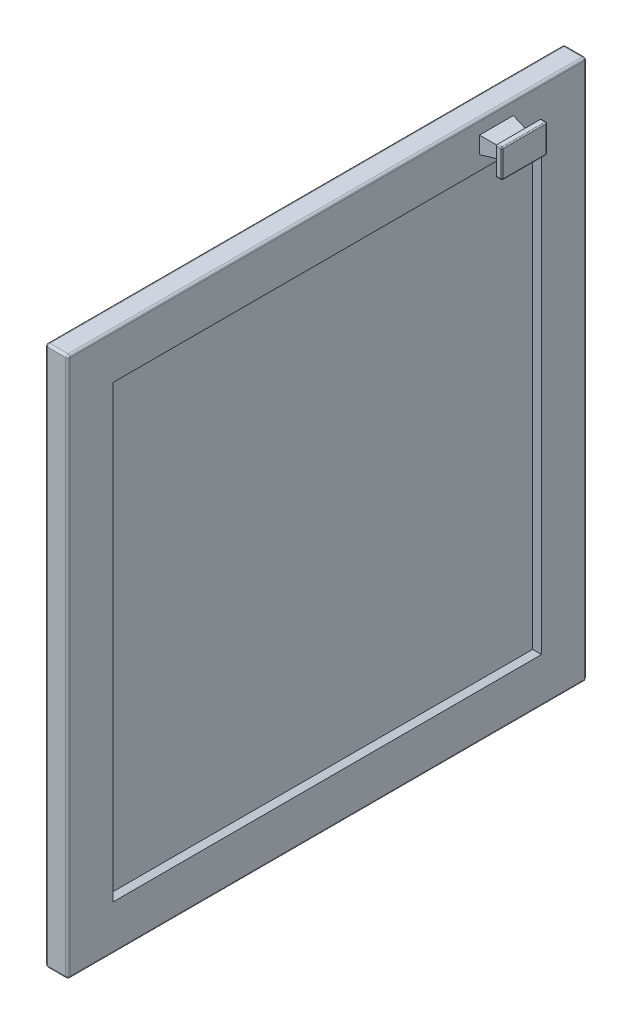
SolidWorks part; units mm, degrees
ref_plane "Front Plane" through (0, 0, 0) normal (1, 0, 0) x (0, 1, 0)
ref_plane "Top Plane" through (0, 0, 0) normal (0, 0, 1) x (0, 1, 0)
ref_plane "Right Plane" through (0, 0, 0) normal (0, 1, 0) x (-1, 0, 0)
sketch "Sketch1" plane through (0, 0, 0) normal (1, 0, 0) x (0, 1, 0)
  line L1 (0, 0) -> (479, 0)
  line L2 (0, 0) -> (0, 460)
  line L3 (0, 460) -> (479, 460)
  line L4 (479, 0) -> (479, 460)
  dimension "D1" = 460
  dimension "D2" = 479
extrude "Boss-Extrude1" add sketch "Sketch1" along normal mid plane 20
sketch "Sketch2" plane through (10, 0, 0) normal (1, 0, 0) x (0, 1, 0)
  line L8 (40, 420) -> (40, 40)
  line L9 (40, 40) -> (439, 40)
  line L10 (439, 40) -> (439, 420)
  line L11 (439, 420) -> (40, 420)
  line L12 (40, 420) -> (40, 40)
  line L13 (40, 40) -> (439, 40)
  line L14 (439, 40) -> (439, 420)
  line L15 (439, 420) -> (40, 420)
  dimension "D1" = 40
extrude "Cut-Extrude1" cut sketch "Sketch2" against normal blind 5 draft 30
mirror "Mirror1" about plane through (0, 0, 0) normal (1, 0, 0) of "Cut-Extrude1"
sketch "Sketch3" plane through (10, 0, 0) normal (1, 0, 0) x (0, 1, 0)
  line L0 (0, 0) -> (479, 0) construction
  line L1 (446.5, 100) -> (471.5, 100) construction
  line L2 (446.5, 100) -> (446.5, 60) construction
  line L3 (446.5, 60) -> (471.5, 60) construction
  line L4 (471.5, 100) -> (471.5, 60) construction
  line L5 (446.5, 100) -> (471.5, 60) construction
  line L6 (446.5, 60) -> (471.5, 100) construction
  line L8 (479, 0) -> (479, 460) construction
  line L10 (451.5, 65) -> (466.5, 65)
  line L11 (451.5, 65) -> (451.5, 95)
  line L12 (451.5, 95) -> (466.5, 95)
  line L13 (466.5, 65) -> (466.5, 95)
  line L14 (451.5, 65) -> (466.5, 95) construction
  line L15 (451.5, 95) -> (466.5, 65) construction
  point P0 (459, 80)
  point P5 (459, 80)
  dimension "D1" = 25
  dimension "D2" = 40
  dimension "D3" = 80
  dimension "D4" = 20
  dimension "D5" = 5
  dimension "D6" = 10
extrude "Boss-Extrude2" add sketch "Sketch3" along normal blind 20 draft 10
sketch "Sketch4" plane through (30, 0, 0) normal (1, 0, 0) x (0, 1, 0)
  line L0 (446.5, 60) -> (471.5, 60) construction
  line L1 (471.5, 100) -> (471.5, 60) construction
  line L2 (446.5, 100) -> (446.5, 60) construction
  line L3 (446.5, 100) -> (471.5, 100) construction
  line L4 (446.5, 60) -> (471.5, 60)
  line L5 (471.5, 100) -> (471.5, 60)
  line L6 (446.5, 100) -> (446.5, 60)
  line L7 (446.5, 100) -> (471.5, 100)
extrude "Boss-Extrude3" add sketch "Sketch4" along normal blind 5
fillet "Fillet3" radius 2 12 edges at (10, 479, 230) (-10, 479, 230) (10, 239.5, 0) (0, 479, 0) (-10, 239.5, 0) (10, 0, 230) (0, 0, 0) (-10, 0, 230) (0, 479, 460) (10, 239.5, 460) (0, 0, 460) (-10, 239.5, 460)
fillet "Fillet4" radius 1 8 edges at (35, 459, 100) (35, 471.5, 80) (35, 459, 60) (35, 446.5, 80) (32.5, 446.5, 100) (32.5, 446.5, 60) (32.5, 471.5, 60) (32.5, 471.5, 100)
